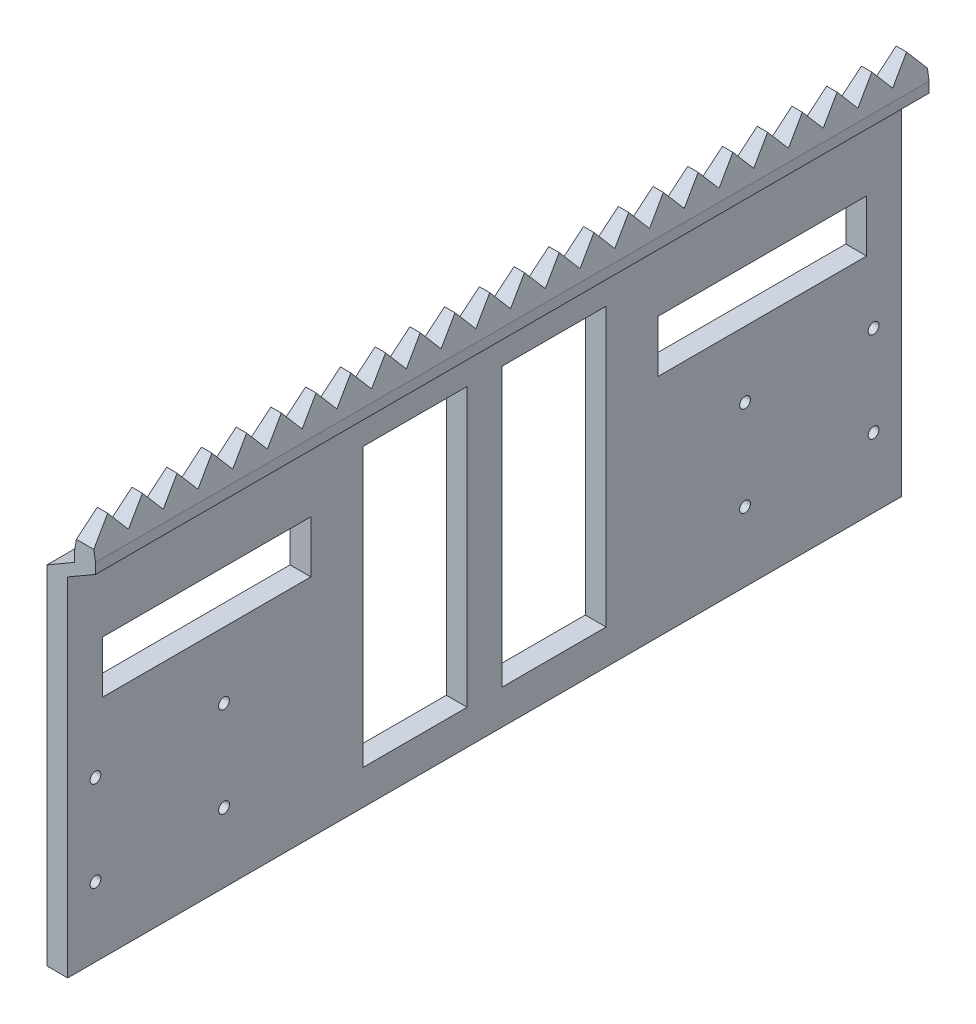
SolidWorks part; units mm, degrees
ref_plane "前视基准面" through (0, 0, 0) normal (0, 0, 1) x (1, 0, 0)
ref_plane "上视基准面" through (0, 0, 0) normal (0, 1, 0) x (1, 0, 0)
ref_plane "右视基准面" through (0, 0, 0) normal (1, 0, 0) x (0, 0, -1)
sketch "草图1" plane through (0, 0, 0) normal (1, 0, 0) x (0, 0, -1)
  line L1 (0, 0) -> (240, 0)
  line L2 (0, 0) -> (0, -100)
  line L3 (0, -100) -> (240, -100)
  line L4 (240, 0) -> (240, -100)
  dimension "D1" = 240
  dimension "D2" = 100
extrude "凸台-拉伸1" add sketch "草图1" along normal blind 6
sketch "草图2" plane through (6, 0, 0) normal (1, 0, 0) x (0, 0, -1)
  line L0 (0, 0) -> (0, -100) construction
  line L1 (8, -54) -> (45, -54) construction
  line L2 (8, -54) -> (8, -80) construction
  line L3 (8, -80) -> (45, -80) construction
  line L4 (45, -54) -> (45, -80) construction
  line L5 (240, 0) -> (0, 0) construction
  line L6 (120, 0) -> (120, -100) construction
  line L7 (0, -100) -> (240, -100) construction
  line L8 (195, -54) -> (195, -80) construction
  line L9 (232, -80) -> (195, -80) construction
  line L10 (232, -54) -> (232, -80) construction
  line L11 (232, -54) -> (195, -54) construction
  circle A0 centre (8, -54) radius 1.55
  circle A1 centre (45, -80) radius 1.55
  circle A2 centre (45, -54) radius 1.55
  circle A3 centre (8, -80) radius 1.55
  circle A4 centre (232, -80) radius 1.55
  circle A5 centre (195, -54) radius 1.55
  circle A6 centre (195, -80) radius 1.55
  circle A7 centre (232, -54) radius 1.55
  dimension "D5" = 3.1
  dimension "D1" = 8
  dimension "D2" = 54
  dimension "D3" = 37
  dimension "D4" = 26
extrude "切除-拉伸1" cut sketch "草图2" against normal through all
sketch "草图3" plane through (6, 0, 0) normal (1, 0, 0) x (0, 0, -1)
  line L0 (120, 0) -> (120, -100) construction
  line L1 (10, -20) -> (70, -20)
  line L2 (10, -20) -> (10, -35)
  line L3 (10, -35) -> (70, -35)
  line L4 (70, -20) -> (70, -35)
  line L5 (240, 0) -> (0, 0) construction
  line L6 (0, -100) -> (240, -100) construction
  line L7 (0, 0) -> (0, -100) construction
  line L8 (170, -20) -> (170, -35)
  line L9 (230, -35) -> (170, -35)
  line L10 (230, -20) -> (230, -35)
  line L11 (230, -20) -> (170, -20)
  dimension "D1" = 10
  dimension "D2" = 20
  dimension "D3" = 15
  dimension "D4" = 60
extrude "切除-拉伸2" cut sketch "草图3" against normal through all
sketch "草图4" plane through (6, 0, 0) normal (1, 0, 0) x (0, 0, -1)
  line L0 (120, 0) -> (120, -100) construction
  line L1 (85, -10) -> (115, -10)
  line L2 (85, -10) -> (85, -90)
  line L3 (85, -90) -> (115, -90)
  line L4 (115, -10) -> (115, -90)
  line L5 (240, 0) -> (0, 0) construction
  line L6 (0, -100) -> (240, -100) construction
  line L7 (0, 0) -> (0, -100) construction
  line L8 (125, -10) -> (125, -90)
  line L9 (155, -90) -> (125, -90)
  line L10 (155, -10) -> (155, -90)
  line L11 (155, -10) -> (125, -10)
  dimension "D1" = 10
  dimension "D2" = 10
  dimension "D3" = 85
  dimension "D4" = 30
extrude "切除-拉伸3" cut sketch "草图4" against normal through all contours L4 L1 L2 L3 | L8 L9 L10 L11
sketch "草图5" plane through (0, 0, 0) normal (-1, 0, 0) x (0, 0, 1)
  circle A0 centre (-195, -80) radius 3
  circle A1 centre (-232, -80) radius 3
  circle A2 centre (-195, -54) radius 3
  circle A3 centre (-232, -54) radius 3
  circle A4 centre (-45, -80) radius 3
  circle A5 centre (-8, -80) radius 3
  circle A6 centre (-8, -54) radius 3
  circle A7 centre (-45, -54) radius 3
  dimension "D1" = 6
extrude "切除-拉伸4" cut sketch "草图5" against normal blind 3
sketch "草图6" plane through (6, 0, 0) normal (1, 0, 0) x (0, 0, -1)
  line L0 (0, 0) -> (0, -100) construction
  line L1 (240, 0) -> (0, 0)
  line L2 (240, 0) -> (240, -7)
  line L3 (240, -7) -> (0, -7)
  line L4 (0, 0) -> (0, -7)
  dimension "D1" = 7
extrude "凸台-拉伸2" [suppressed] add sketch "草图6" along normal blind 10 separate body
sketch "草图8" plane through (0, 0, -240) normal (0, 0, -1) x (-1, 0, 0)
  line L0 (-6, 0) -> (-14, 4.6188)
  line L1 (-14, 4.6188) -> (-14, 16.6188)
  line L2 (-14, 16.6188) -> (-8, 16.6188)
  line L3 (-8, 16.6188) -> (-8, 4.6188)
  line L4 (-8, 4.6188) -> (0, 0)
  line L5 (0, 0) -> (-6, 0)
  line L6 (-6, -100) -> (-6, 0) construction
  dimension "D1" = 120
  dimension "D2" = 6
  dimension "D3" = 12
  dimension "D4" = 8
extrude "凸台-拉伸3" add sketch "草图8" against normal up to surface (240 mm away) up to face at (3, -50, 0)
sketch "草图9" plane through (14, 0, 0) normal (1, 0, 0) x (0, 0, -1)
  line L0 (0, 16.6188) -> (0, 10.6188)
  line L1 (0, 4.6188) -> (0, 16.6188) construction
  line L2 (0, 10.6188) -> (5, 16.6188)
  line L3 (0, 16.6188) -> (240, 16.6188) construction
  line L4 (5, 16.6188) -> (0, 16.6188)
  dimension "D1" = 5
  dimension "D2" = 6
extrude "切除-拉伸5" cut sketch "草图9" against normal blind 10
sketch "草图10" plane through (14, 0, 0) normal (1, 0, 0) x (0, 0, -1)
  line L0 (5, 16.6188) -> (10, 10.6188)
  line L1 (10, 10.6188) -> (15, 16.6188)
  line L2 (5, 16.6188) -> (240, 16.6188) construction
  line L3 (15, 16.6188) -> (5, 16.6188)
  line L4 (0, 10.6188) -> (10, 10.6188) construction
  dimension "D1" = 10
extrude "切除-拉伸6" cut sketch "草图10" against normal blind 10
pattern_linear "阵列(线性)1" count 23 spacing 10 along (0, 0, -1) of "切除-拉伸6"
sketch "草图11" plane through (14, 0, 0) normal (1, 0, 0) x (0, 0, -1)
  line L0 (235, 16.6188) -> (240, 10.6188)
  line L1 (240, 16.6188) -> (240, 4.6188) construction
  line L2 (240, 10.6188) -> (240, 16.6188)
  line L3 (240, 16.6188) -> (235, 16.6188)
  line L4 (230, 10.6188) -> (240, 10.6188) construction
extrude "切除-拉伸7" cut sketch "草图11" against normal blind 10
sketch "草图12" plane through (0, 0, -240) normal (0, 0, -1) x (-1, 0, 0)
  line L0 (-14, 7.6188) -> (-12.5, 16.6188)
  line L1 (-14, 10.6188) -> (-14, 4.6188) construction
  line L2 (-8, 16.6188) -> (-14, 16.6188) construction
  line L4 (-9.5, 16.6188) -> (-8, 7.6188)
  line L5 (-8, 4.6188) -> (-8, 10.6188) construction
  line L7 (-12.5, 16.6188) -> (-14, 16.6188)
  line L8 (-14, 16.6188) -> (-14, 7.6188)
  line L9 (-9.5, 16.6188) -> (-8, 16.6188)
  line L10 (-8, 16.6188) -> (-8, 7.6188)
  dimension "D1" = 3
extrude "切除-拉伸8" cut sketch "草图12" against normal through all
